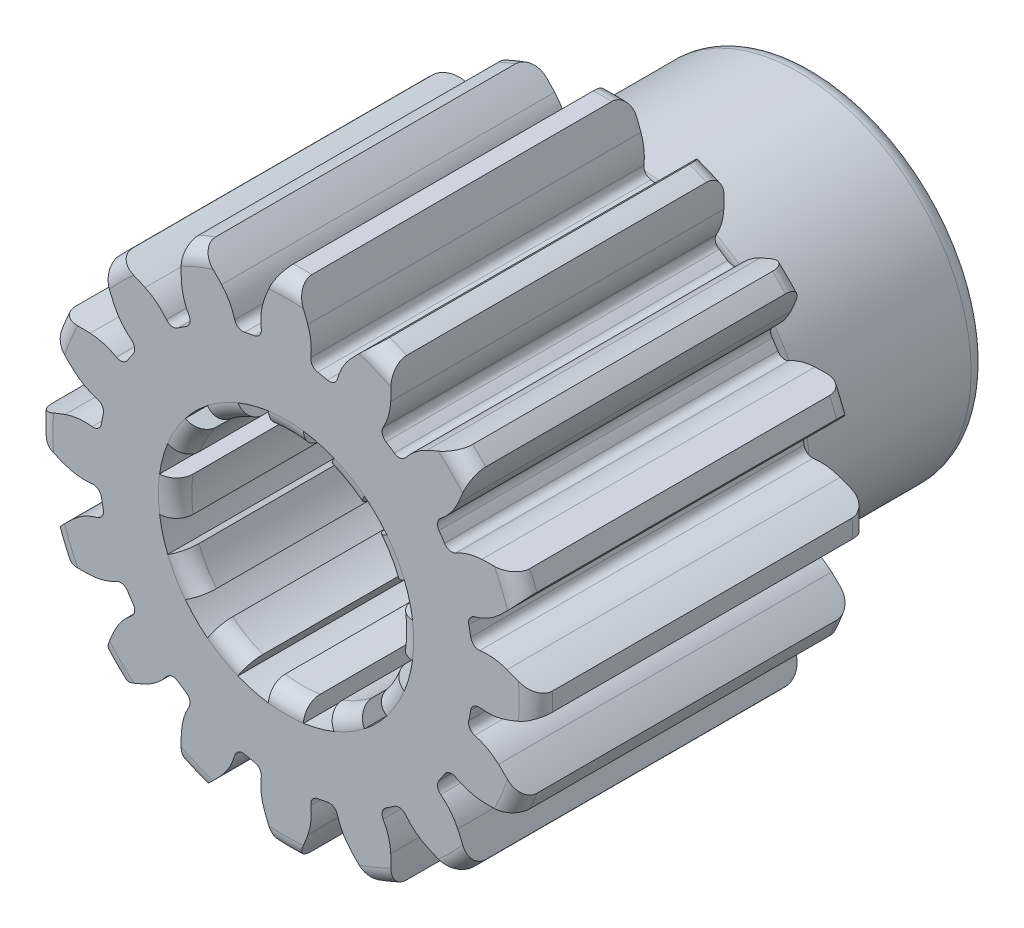
SolidWorks part; units mm, degrees
material "Chrome Stainless Steel"
ref_plane "Front Plane" through (0, 0, 0) normal (0, 0, 1) x (1, 0, 0)
ref_plane "Top Plane" through (0, 0, 0) normal (0, 1, 0) x (1, 0, 0)
ref_plane "Right Plane" through (0, 0, 0) normal (1, 0, 0) x (0, 0, -1)
sketch "Sketch1" plane through (0, 0, 0) normal (0, 0, 1) x (1, 0, 0)
  line L0 (9.7438, 26.8933) -> (12.1265, 25.9064)
  line L1 (-28.575, 0) -> (28.575, 0) construction
  line L2 (0, 28.575) -> (0, 25.4) construction
  line L3 (0, 25.4) -> (0, 21.4312) construction
  line L4 (-1.2895, 28.575) -> (1.2895, 28.575)
  line L5 (-1.2895, 28.575) -> (-4.0287, 21.0492)
  line L6 (1.2895, 28.575) -> (4.0287, 21.0492)
  line L7 (9.7438, 26.8933) -> (4.3331, 20.9886)
  line L8 (-4.9873, -28.575) -> (4.9873, -28.575) construction
  line L9 (4.9873, -28.575) -> (0, -37.2132) construction
  line L10 (0, -37.2132) -> (-4.9873, -28.575) construction
  line L11 (0, -37.2132) -> (0, -36.8695) construction
  line L12 (-0.1984, -36.8695) -> (0.1984, -36.8695) construction
  line L13 (0, -28.9187) -> (0, -28.575) construction
  line L14 (10.9352, 26.3999) -> (0, 0) construction
  line L15 (4.7889, -28.9187) -> (-4.7889, -28.9187) construction
  line L16 (12.1265, 25.9064) -> (11.7772, 17.9052)
  line L17 (-4.8881, -28.7469) -> (4.8881, -28.7469) construction
  line L18 (0, 0) -> (-2.8345, 22.1831) construction
  line L19 (0, 0) -> (5.8704, 21.5792) construction
  circle A0 centre (0, 0) radius 28.575
  circle A1 centre (0, 0) radius 25.4 construction
  circle A2 centre (0, 0) radius 12.7
  circle A3 centre (0, 0) radius 21.4312
  arc A4 (-2.4896, 25.2777) -> (2.4896, 25.2777) centre (0, 0) cw
  circle A5 centre (0, 0) radius 19.812 construction
  arc A6 (-3.6185, 21.1236) -> (-2.8345, 22.1831) centre (-3.7793, 22.0624) ccw
  circle A8 centre (0, 0) radius 22.225 construction
  arc A10 (-2.4896, 25.2777) -> (-2.8345, 22.1831) centre (3.7138, 23.0198) ccw
  arc A11 (-1.0438, 28.575) -> (-2.4896, 25.2777) centre (23.8914, 15.6758) ccw
  arc A13 (4.7406, 20.9004) -> (5.8704, 21.5792) centre (4.9513, 21.8293) ccw
  arc A15 (7.3732, 24.3063) -> (5.8704, 21.5792) centre (12.2404, 19.8464) ccw
  arc A16 (9.9708, 26.7993) -> (7.3732, 24.3063) centre (28.0717, 5.3397) ccw
  arc A17 (3.6185, 21.1236) -> (2.8345, 22.1831) centre (3.7793, 22.0624) cw
  arc A18 (2.4896, 25.2777) -> (2.8345, 22.1831) centre (-3.7138, 23.0198) cw
  arc A19 (1.0438, 28.575) -> (2.4896, 25.2777) centre (-23.8914, 15.6758) cw
  arc A20 (11.4267, 18.1309) -> (11.1079, 19.4098) centre (11.9346, 18.9367) cw
  arc A21 (11.9735, 22.4008) -> (11.1079, 19.4098) centre (5.3782, 22.6888) cw
  arc A22 (11.8996, 26.0004) -> (11.9735, 22.4008) centre (-16.074, 23.6254) cw
  point P5 (0, 28.575)
  point P8 (10.9352, 26.3999)
  point P9 (20.2056, 20.2056)
  point P10 (26.3999, 10.9352)
  point P11 (28.575, 0)
  point P12 (26.3999, -10.9352)
  point P13 (20.2056, -20.2056)
  point P14 (10.9352, -26.3999)
  point P15 (0, -28.575)
  point P16 (-10.9352, -26.3999)
  point P17 (-20.2056, -20.2056)
  point P18 (-26.3999, -10.9352)
  point P19 (-28.575, 0)
  point P20 (-26.3999, 10.9352)
  point P21 (-20.2056, 20.2056)
  point P22 (0, 0)
  point P37 (-4.9873, -28.575)
  point P47 (0, -28.7469)
  point P48 (-10.9352, 26.3999)
  point P49 (4.9873, -28.575)
  point P53 (14.9619, -28.575)
  point P54 (24.9365, -28.575)
  point P55 (34.911, -28.575)
  point P56 (44.8856, -28.575)
  point P57 (54.8602, -28.575)
  point P58 (64.8348, -28.575)
  point P81 (0, 19.812)
  dimension "OD" = 57.15
  dimension "Shaft Diameter" = 25.4
  dimension "Pitch Diameter" = 50.8
  dimension "Hub Diameter" = 39.624
  dimension "D4" = 0.9525
  dimension "Driven Dim* Addendum (a)" = 3.175
  dimension "Dedendum (b)" = 3.9688
  dimension "D2" = 9.9746
  dimension "D3" = 0.3969
  dimension "Pressure Angle" = 20
  dimension "Clearance" = 0.7937
  dimension "D5" = 22.5
  dimension "D1" = 4.9873
  dimension "Gear Pitch" = 8
  dimension "Teeth" = 16
sketch "Sketch2" plane through (0, 0, 0) normal (1, 0, 0) x (0, 0, -1)
  line L0 (-30.226, 26.67) -> (-30.226, -26.67)
  line L1 (-28.321, -28.575) -> (5.969, -28.575)
  line L2 (7.874, -26.67) -> (7.874, -21.717)
  line L3 (9.779, -19.812) -> (28.321, -19.812)
  line L4 (30.226, -17.907) -> (30.226, 17.907)
  line L5 (28.321, 19.812) -> (9.779, 19.812)
  line L6 (7.874, 21.717) -> (7.874, 26.67)
  line L7 (5.969, 28.575) -> (-28.321, 28.575)
  line L8 (30.226, 0) -> (-30.226, 0) construction
  line L9 (-54.6035, 0) -> (48.2754, 0) construction
  line L10 (7.874, 19.812) -> (-30.226, 19.812) construction
  line L13 (30.226, 12.7) -> (0, 12.7) construction
  line L15 (-30.226, 12.7) -> (0, 12.7) construction
  line L17 (30.226, -12.7) -> (0, -12.7) construction
  line L18 (0, -12.7) -> (-30.226, -12.7) construction
  arc A0 (-30.226, -26.67) -> (-28.321, -28.575) centre (-28.321, -26.67) ccw
  arc A1 (5.969, -28.575) -> (7.874, -26.67) centre (5.969, -26.67) ccw
  arc A2 (7.874, -21.717) -> (9.779, -19.812) centre (9.779, -21.717) cw
  arc A3 (30.226, -17.907) -> (28.321, -19.812) centre (28.321, -17.907) cw
  arc A4 (7.874, 21.717) -> (9.779, 19.812) centre (9.779, 21.717) ccw
  arc A5 (-30.226, 26.67) -> (-28.321, 28.575) centre (-28.321, 26.67) cw
  arc A6 (5.969, 28.575) -> (7.874, 26.67) centre (5.969, 26.67) cw
  arc A7 (28.321, 19.812) -> (30.226, 17.907) centre (28.321, 17.907) cw
  point P40 (30.226, 19.812)
  dimension "Radius" = 1.905
  dimension "Hub Width" = 22.352
  dimension "Overall Width" = 60.452
sketch "Sketch3" plane through (0, 0, 0) normal (1, 0, 0) x (0, 0, -1)
  line L0 (28.321, 12.7) -> (-28.321, 12.7)
  line L1 (30.226, -17.907) -> (30.226, 17.907) construction
  line L2 (28.321, 19.812) -> (9.779, 19.812) construction
  line L3 (7.874, 21.717) -> (7.874, 26.67) construction
  line L4 (5.969, 28.575) -> (-28.321, 28.575) construction
  line L5 (-30.226, 26.67) -> (-30.226, -26.67) construction
  line L6 (30.226, 14.605) -> (30.226, 17.907)
  line L7 (28.321, 19.812) -> (9.779, 19.812)
  line L8 (7.874, 21.717) -> (7.874, 26.67)
  line L9 (5.969, 28.575) -> (-28.321, 28.575)
  line L10 (-30.226, 26.67) -> (-30.226, 14.605)
  line L11 (30.226, 12.7) -> (0, 12.7) construction
  arc A8 (30.226, 17.907) -> (28.321, 19.812) centre (28.321, 17.907) ccw construction
  arc A9 (7.874, 21.717) -> (9.779, 19.812) centre (9.779, 21.717) ccw construction
  arc A10 (7.874, 26.67) -> (5.969, 28.575) centre (5.969, 26.67) ccw construction
  arc A11 (-28.321, 28.575) -> (-30.226, 26.67) centre (-28.321, 26.67) ccw construction
  arc A12 (30.226, 17.907) -> (28.321, 19.812) centre (28.321, 17.907) ccw
  arc A13 (7.874, 21.717) -> (9.779, 19.812) centre (9.779, 21.717) ccw
  arc A14 (7.874, 26.67) -> (5.969, 28.575) centre (5.969, 26.67) ccw
  arc A15 (-28.321, 28.575) -> (-30.226, 26.67) centre (-28.321, 26.67) ccw
  arc A16 (-30.226, 14.605) -> (-28.321, 12.7) centre (-28.321, 14.605) ccw
  arc A17 (28.321, 12.7) -> (30.226, 14.605) centre (28.321, 14.605) ccw
revolve "Revolve1" add sketch "Sketch3" angle 360 about L8
sketch "Sketch4" plane through (0, 0, 30.226) normal (0, 0, 1) x (1, 0, 0)
  circle A9 centre (0, 0) radius 28.575 construction
  circle A21 centre (0, 0) radius 21.4312 construction
  arc A22 (4.7406, 20.9004) -> (5.8704, 21.5792) centre (4.9513, 21.8293) ccw construction
  arc A23 (7.3732, 24.3063) -> (5.8704, 21.5792) centre (12.2404, 19.8464) ccw construction
  arc A24 (9.9708, 26.7993) -> (7.3732, 24.3063) centre (28.0717, 5.3397) ccw construction
  arc A25 (2.4896, 25.2777) -> (1.0438, 28.575) centre (-23.8914, 15.6758) ccw construction
  arc A26 (2.8345, 22.1831) -> (2.4896, 25.2777) centre (-3.7138, 23.0198) ccw construction
  arc A27 (2.8345, 22.1831) -> (3.6185, 21.1236) centre (3.7793, 22.0624) ccw construction
  arc A28 (9.9541, 26.7852) -> (1.0539, 28.5556) centre (0, 0) ccw
  arc A29 (4.7406, 20.9004) -> (3.6185, 21.1236) centre (0, 0) ccw
  arc A30 (4.7406, 20.9004) -> (5.8704, 21.5792) centre (4.9513, 21.8293) ccw
  arc A31 (7.3732, 24.3063) -> (5.8704, 21.5792) centre (12.2404, 19.8464) ccw
  arc A32 (9.9541, 26.7852) -> (7.3732, 24.3063) centre (28.0717, 5.3397) ccw
  arc A33 (2.4896, 25.2777) -> (1.0539, 28.5556) centre (-23.8914, 15.6758) ccw
  arc A34 (2.8345, 22.1831) -> (2.4896, 25.2777) centre (-3.7138, 23.0198) ccw
  arc A35 (2.8345, 22.1831) -> (3.6185, 21.1236) centre (3.7793, 22.0624) ccw
extrude "Cut-Extrude1" cut sketch "Sketch4" against normal through all both and the other way through all
pattern_circular "CirPattern1" count 16 every 22.5 about axis through (0, 0, 0) along (0, 0, 1) of "Cut-Extrude1"
ref_plane "Plane1" through (0, 0, -30.226) normal (0, 0, -1) x (-1, 0, 0)
sketch "Sketch5" plane through (0, 0, -30.226) normal (0, 0, -1) x (-1, 0, 0)
  line L0 (0, 14.605) -> (0, 12.7)
  line L1 (-2, 14.4674) -> (-2, 12.5415)
  line L2 (2, 14.4674) -> (2, 12.5415)
  line L3 (2, 15.3434) -> (2, 11.6314) construction
  line L4 (0, 15.3434) -> (0, 11.6314) construction
  line L5 (-2, 15.3434) -> (-2, 11.6314) construction
  line L6 (7.3025, 12.6483) -> (6.35, 10.9985)
  line L7 (8.9658, 11.5291) -> (8.0028, 9.8613)
  line L8 (5.5017, 13.5291) -> (4.5387, 11.8613)
  line L9 (12.6483, 7.3025) -> (10.9985, 6.35)
  line L10 (13.5291, 5.5017) -> (11.8613, 4.5387)
  line L11 (11.5291, 8.9658) -> (9.8613, 8.0028)
  line L12 (14.605, 0) -> (12.7, 0)
  line L13 (14.4674, -2) -> (12.5415, -2)
  line L14 (14.4674, 2) -> (12.5415, 2)
  line L15 (12.6483, -7.3025) -> (10.9985, -6.35)
  line L16 (11.5291, -8.9658) -> (9.8613, -8.0028)
  line L17 (13.5291, -5.5017) -> (11.8613, -4.5387)
  line L18 (7.3025, -12.6483) -> (6.35, -10.9985)
  line L19 (5.5017, -13.5291) -> (4.5387, -11.8613)
  line L20 (8.9658, -11.5291) -> (8.0028, -9.8613)
  line L21 (0, -14.605) -> (0, -12.7)
  line L22 (-2, -14.4674) -> (-2, -12.5415)
  line L23 (2, -14.4674) -> (2, -12.5415)
  line L24 (-7.3025, -12.6483) -> (-6.35, -10.9985)
  line L25 (-8.9658, -11.5291) -> (-8.0028, -9.8613)
  line L26 (-5.5017, -13.5291) -> (-4.5387, -11.8613)
  line L27 (-12.6483, -7.3025) -> (-10.9985, -6.35)
  line L28 (-13.5291, -5.5017) -> (-11.8613, -4.5387)
  line L29 (-11.5291, -8.9658) -> (-9.8613, -8.0028)
  line L30 (-14.605, 0) -> (-12.7, 0)
  line L31 (-14.4674, 2) -> (-12.5415, 2)
  line L32 (-14.4674, -2) -> (-12.5415, -2)
  line L33 (-12.6483, 7.3025) -> (-10.9985, 6.35)
  line L34 (-11.5291, 8.9658) -> (-9.8613, 8.0028)
  line L35 (-13.5291, 5.5017) -> (-11.8613, 4.5387)
  line L36 (-7.3025, 12.6483) -> (-6.35, 10.9985)
  line L37 (-5.5017, 13.5291) -> (-4.5387, 11.8613)
  line L38 (-8.9658, 11.5291) -> (-8.0028, 9.8613)
  circle A0 centre (0, 0) radius 14.605
  circle A1 centre (0, 0) radius 12.7
  point P85 (0, 0)
  dimension "D1" = 2
  dimension "D2" = 2
  dimension "D3" = 12
extrude "Cut-Extrude2" cut sketch "Sketch5" against normal up to next contours A1 L8 A0 L2 | A1 L11 A0 L7 | A1 L14 A0 L10 | A1 L17 A0 L13 | A1 L20 A0 L16 | A1 L23 A0 L19 | A1 L26 A0 L22 | A1 L29 A0 L25 | A1 L32 A0 L28 | A1 L35 A0 L31 | A1 L38 A0 L34 | A1 L1 A0 L37
equation "\"D3@Sketch1\"=(1/\"Gear Pitch@Sketch1\")/8"
equation "\"D2@Sketch1\"=3.1416/\"Gear Pitch@Sketch1\""
equation "\"Dedendum (b)@Sketch1\"=1.25/\"Gear Pitch@Sketch1\""
equation "\"D1@Sketch1\"=1.5708/\"Gear Pitch@Sketch1\""
equation "\"D4@Sketch1\"=.3/\"Gear Pitch@Sketch1\""
equation "\"Clearance@Sketch1\" = .25 / \"Gear Pitch@Sketch1\""
equation "\"D1@CirPattern1\"=\"Teeth@Sketch1\""
equation "\"D5@Sketch1\"=360/\"Teeth@Sketch1\""
equation "\"D2@CirPattern1\"=\"D5@Sketch1\""
equation "\"Radius@Sketch2\"=.6/\"Gear Pitch@Sketch1\""
